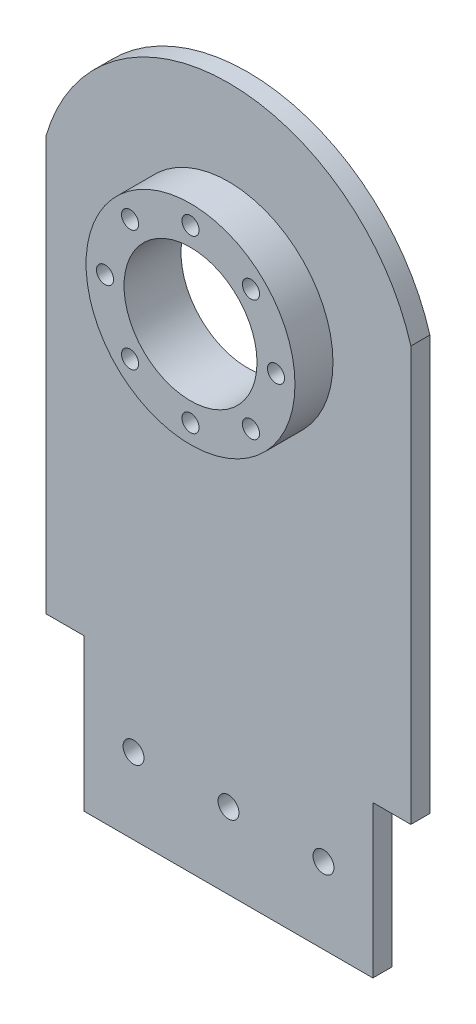
SolidWorks part; units mm, degrees
material "6061 合金"
ref_plane "前视基准面" through (0, 0, 0) normal (0, 0, 1) x (1, 0, 0)
ref_plane "上视基准面" through (0, 0, 0) normal (0, 1, 0) x (1, 0, 0)
ref_plane "右视基准面" through (0, 0, 0) normal (1, 0, 0) x (0, 0, -1)
other "Configuration Table"
sketch "草图1" plane through (0, 0, 0) normal (0, 0, 1) x (1, 0, 0)
  line L0 (0, 0) -> (0, 150.9585) construction
  line L3 (-48, 109.07) -> (-48, 0)
  line L4 (-48, 0) -> (48, 0)
  line L5 (48, 109.07) -> (48, 0)
  circle A0 centre (0, 95.07) radius 17.5
  arc A2 (48, 109.07) -> (-48, 109.07) centre (0, 95.07) ccw
  dimension "D3" = 35
  dimension "D4" = 50
  dimension "D1" = 96
  dimension "D2" = 95.07
extrude "凸台-拉伸1" add sketch "草图1" along normal blind 5
sketch "草图2" plane through (0, 0, 0) normal (0, -1, 0) x (1, 0, 0)
  line L0 (-53.8408, 2.5) -> (58.1589, 2.5) construction
  line L1 (0, 20.308) -> (0, -17.9139) construction
  line L2 (-48, 5) -> (48, 5) construction
  line L3 (-48, 0) -> (48, 0) construction
  circle A0 centre (35, 2.5) radius 2.75
  circle A1 centre (-35, 2.5) radius 2.75
  dimension "D2" = 5.5
  dimension "D1" = 70
extrude "切除-拉伸1" [suppressed] cut sketch "草图2" against normal blind 50
sketch "草图5" plane through (0, 0, 5) normal (0, 0, 1) x (1, 0, 0)
  line L0 (0, 0) -> (0, 169.4961) construction
  line L2 (-58, 0) -> (58, 0)
  line L3 (-58, 0) -> (-58, -50)
  line L4 (-58, -50) -> (58, -50)
  line L5 (58, 0) -> (58, -50)
  dimension "D1" = 116
  dimension "D2" = 50
extrude "碳板突出" [suppressed] add sketch "草图5" against normal up to surface (5 mm away)
sketch "草图6" [suppressed] plane through (0, 0, 5) normal (0, 0, 1) x (1, 0, 0)
  line L0 (0, 0) -> (0, -61.5724) construction
  line L2 (45, -5) -> (50.2, -5)
  line L3 (45, -5) -> (45, -20.2)
  line L4 (45, -20.2) -> (50.2, -20.2)
  line L5 (50.2, -5) -> (50.2, -20.2)
  line L6 (45, -30.2) -> (50.2, -30.2)
  line L7 (45, -30.2) -> (45, -45.4)
  line L8 (45, -45.4) -> (50.2, -45.4)
  line L9 (50.2, -30.2) -> (50.2, -45.4)
  line L10 (-50.2, -30.2) -> (-50.2, -45.4)
  line L11 (-45, -45.4) -> (-50.2, -45.4)
  line L12 (-45, -30.2) -> (-45, -45.4)
  line L13 (-45, -30.2) -> (-50.2, -30.2)
  line L14 (-50.2, -5) -> (-50.2, -20.2)
  line L15 (-45, -20.2) -> (-50.2, -20.2)
  line L16 (-45, -5) -> (-45, -20.2)
  line L17 (-45, -5) -> (-50.2, -5)
  line L18 (58, 0) -> (48, 0) construction
  dimension "D1" = 5.2
  dimension "D2" = 15.2
  dimension "D3" = 15.2
  dimension "D4" = 45
  dimension "D5" = 10
  dimension "D6" = 5
extrude "切除-拉伸4" [suppressed] cut sketch "草图6" against normal through all both
sketch "草图7" [suppressed] plane through (0, 0, 5) normal (0, 0, 1) x (1, 0, 0)
  line L0 (50.2, -20.2) -> (50.2, -5) construction
  line L1 (45, -5) -> (45, -20.2) construction
  line L2 (50.2, -45.4) -> (50.2, -30.2) construction
  line L3 (45, -30.2) -> (45, -45.4) construction
  line L4 (50.2, -5) -> (45, -5) construction
  line L5 (45, -20.2) -> (50.2, -20.2) construction
  line L6 (50.2, -30.2) -> (45, -30.2) construction
  line L7 (45, -45.4) -> (50.2, -45.4) construction
  line L8 (0, 0) -> (0, -72.6402) construction
  circle A0 centre (50.2, -6.55) radius 1.55
  circle A1 centre (50.2, -18.65) radius 1.55
  circle A2 centre (45, -6.55) radius 1.55
  circle A3 centre (45, -18.65) radius 1.55
  circle A4 centre (50.2, -31.75) radius 1.55
  circle A5 centre (45, -31.75) radius 1.55
  circle A6 centre (50.2, -43.85) radius 1.55
  circle A7 centre (45, -43.85) radius 1.55
  circle A8 centre (-45, -43.85) radius 1.55
  circle A9 centre (-50.2, -43.85) radius 1.55
  circle A10 centre (-45, -31.75) radius 1.55
  circle A11 centre (-50.2, -31.75) radius 1.55
  circle A12 centre (-45, -18.65) radius 1.55
  circle A13 centre (-45, -6.55) radius 1.55
  circle A14 centre (-50.2, -18.65) radius 1.55
  circle A15 centre (-50.2, -6.55) radius 1.55
  dimension "D1" = 3.1
extrude "切除-拉伸5" [suppressed] cut sketch "草图7" against normal through all both
sketch "草图8" [suppressed] plane through (0, 0, 5) normal (0, 0, 1) x (1, 0, 0)
  line L0 (0, 22.7135) -> (0, -60.4554) construction
  line L1 (58, -50) -> (58, 0) construction
  line L2 (58, -5) -> (63, -5)
  line L3 (58, -5) -> (58, -20)
  line L4 (58, -20) -> (63, -20)
  line L5 (63, -5) -> (63, -20)
  line L6 (58, 0) -> (48, 0) construction
  line L7 (58, -30) -> (63, -30)
  line L8 (58, -30) -> (58, -45)
  line L9 (58, -45) -> (63, -45)
  line L10 (63, -30) -> (63, -45)
  line L11 (-63, -30) -> (-63, -45)
  line L12 (-58, -45) -> (-63, -45)
  line L13 (-58, -30) -> (-58, -45)
  line L14 (-58, -30) -> (-63, -30)
  line L15 (-63, -5) -> (-63, -20)
  line L16 (-58, -20) -> (-63, -20)
  line L17 (-58, -5) -> (-58, -20)
  line L18 (-58, -5) -> (-63, -5)
  dimension "D1" = 5
  dimension "D2" = 15
  dimension "D3" = 5
  dimension "D4" = 10
  dimension "D5" = 15
extrude "碳板榫卯突起" [suppressed] add sketch "草图8" against normal up to surface (5 mm away)
sketch "草图9" [suppressed] plane through (0, 0, 5) normal (0, 0, 1) x (1, 0, 0)
  line L0 (58, -5) -> (58, 0) construction
  line L1 (58, -30) -> (58, -20) construction
  line L2 (58, -50) -> (58, -45) construction
  line L3 (63, -5) -> (58, -5) construction
  line L4 (58, -20) -> (63, -20) construction
  line L5 (63, -30) -> (58, -30) construction
  line L6 (58, -45) -> (63, -45) construction
  line L7 (0, 0) -> (0, -84.76) construction
  circle A0 centre (58, -3.45) radius 1.55
  circle A1 centre (58, -21.55) radius 1.55
  circle A2 centre (58, -28.45) radius 1.55
  circle A3 centre (58, -46.55) radius 1.55
  circle A4 centre (-58, -46.55) radius 1.55
  circle A5 centre (-58, -28.45) radius 1.55
  circle A6 centre (-58, -21.55) radius 1.55
  circle A7 centre (-58, -3.45) radius 1.55
  dimension "D1" = 3.1
extrude "碳板榫卯半圆" [suppressed] cut sketch "草图9" against normal up to surface (5 mm away)
fillet "碳板榫卯圆角" [suppressed] radius 5
sketch "草图10" plane through (0, 0, 5) normal (0, 0, 1) x (1, 0, 0)
  line L0 (0, 87.232) -> (0, -56.3055) construction
  line L1 (-48, 0) -> (48, 0) construction
  line L2 (-38, 0) -> (38, 0)
  line L3 (-38, 0) -> (-38, -40)
  line L4 (-38, -40) -> (38, -40)
  line L5 (38, 0) -> (38, -40)
  circle A0 centre (25, -20) radius 2.75
  circle A1 centre (-25, -20) radius 2.75
  circle A2 centre (0, -20) radius 2.75
  dimension "D3" = 5.5
  dimension "D6" = 5.5
  dimension "D1" = 76
  dimension "D2" = 40
  dimension "D4" = 20
  dimension "D5" = 50
extrude "凸台-拉伸2" add sketch "草图10" against normal up to surface (5 mm away) up to face at (0, 63.535, 0)
sketch "草图11" plane through (0, 0, 5) normal (0, 0, 1) x (1, 0, 0)
  circle A0 centre (0, 95.07) radius 27.5
  circle A1 centre (0, 95.07) radius 17.5 construction
  circle A2 centre (0, 95.07) radius 17.5
  dimension "D1" = 55
extrude "凸台-拉伸3" add sketch "草图11" along normal blind 10
sketch "草图12" plane through (0, 0, 15) normal (0, 0, 1) x (1, 0, 0)
  circle A0 centre (0, 95.07) radius 22.5 construction
  circle A1 centre (0, 117.57) radius 2.25
  circle A2 centre (15.9099, 110.9799) radius 2.25
  circle A3 centre (22.5, 95.07) radius 2.25
  circle A4 centre (15.9099, 79.1601) radius 2.25
  circle A5 centre (0, 72.57) radius 2.25
  circle A6 centre (-15.9099, 79.1601) radius 2.25
  circle A7 centre (-22.5, 95.07) radius 2.25
  circle A8 centre (-15.9099, 110.9799) radius 2.25
  point P6 (0, 95.07)
  point P21 (0, 95.07)
  dimension "D1" = 45
  dimension "D2" = 4.5
  dimension "D3" = 8
extrude "切除-拉伸6" cut sketch "草图12" against normal blind 40
